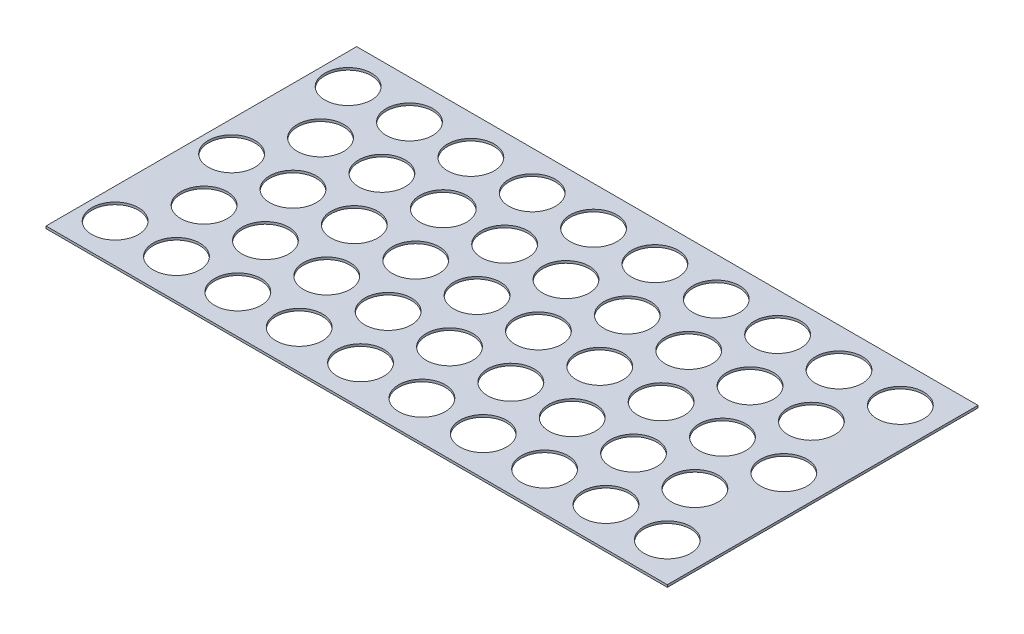
SolidWorks part; units mm, degrees
ref_plane "Front Plane" through (0, 0, 0) normal (0, 0, 1) x (1, 0, 0)
ref_plane "Top Plane" through (0, 0, 0) normal (0, 1, 0) x (1, 0, 0)
ref_plane "Right Plane" through (0, 0, 0) normal (1, 0, 0) x (0, 0, -1)
sketch "Sketch1" plane through (0, 0, 0) normal (0, 1, 0) x (1, 0, 0)
  line L1 (-100.118, 57.1397) -> (103.082, 57.1397)
  line L2 (-100.118, 57.1397) -> (-100.118, -44.4603)
  line L3 (-100.118, -44.4603) -> (103.082, -44.4603)
  line L4 (103.082, 57.1397) -> (103.082, -44.4603)
  dimension "D1" = 203.2
  dimension "D2" = 101.6
extrude "Boss-Extrude2" add sketch "Sketch1" against normal blind 0.762 contours L4 L1 L2 L3
sketch "Sketch2" plane through (0, 0, 0) normal (0, 1, 0) x (1, 0, 0)
  line L0 (103.082, -44.4603) -> (103.082, -31.7603) construction
  line L1 (103.082, -31.7603) -> (90.382, -31.7603)
  line L2 (103.082, -31.7603) -> (-49896.918, -31.7603) construction
  line L3 (90.382, -31.7603) -> (90.382, 6.3397) construction
  line L4 (103.082, -44.4603) -> (103.082, 57.1397)
  line L5 (103.082, 57.1397) -> (-100.118, 57.1397)
  line L6 (-100.118, 57.1397) -> (-100.118, -44.4603)
  line L7 (-100.118, -44.4603) -> (103.082, -44.4603)
  line L8 (103.082, -44.4603) -> (103.082, 57.1397)
  line L9 (103.082, 57.1397) -> (-100.118, 57.1397)
  line L10 (-100.118, 57.1397) -> (-100.118, -44.4603)
  line L11 (-100.118, -44.4603) -> (103.082, -44.4603)
  line L12 (90.382, 6.3397) -> (-49909.618, 6.3397) construction
  line L13 (90.382, 6.3397) -> (90.382, 44.4397) construction
  line L14 (90.382, 44.4397) -> (-49909.618, 44.4397) construction
  line L15 (90.382, -31.7603) -> (80.349, -31.7603) construction
  line L16 (80.349, -31.7603) -> (80.349, 49968.2397) construction
  line L17 (90.382, -31.7603) -> (90.382, -12.7103) construction
  line L18 (90.382, -12.7103) -> (-49909.618, -12.7103) construction
  line L19 (90.382, 6.3397) -> (90.382, 25.3897) construction
  line L20 (90.382, 25.3897) -> (-49909.618, 25.3897) construction
  line L21 (90.382, -12.7103) -> (80.349, -12.7103) construction
  line L22 (80.349, -12.7103) -> (80.349, 25.3897) construction
  circle A0 centre (90.382, -31.7603) radius 7.62
  circle A1 centre (90.382, 6.3397) radius 7.62
  circle A2 centre (90.382, 44.4397) radius 7.62
  circle A3 centre (70.316, -31.7603) radius 7.62
  circle A4 centre (50.25, -31.7603) radius 7.62
  circle A5 centre (30.184, -31.7603) radius 7.62
  circle A6 centre (10.118, -31.7603) radius 7.62
  circle A7 centre (-9.948, -31.7603) radius 7.62
  circle A8 centre (-30.014, -31.7603) radius 7.62
  circle A9 centre (-50.08, -31.7603) radius 7.62
  circle A10 centre (-70.146, -31.7603) radius 7.62
  circle A11 centre (-90.212, -31.7603) radius 7.62
  circle A12 centre (70.316, 6.3397) radius 7.62
  circle A13 centre (50.25, 6.3397) radius 7.62
  circle A14 centre (30.184, 6.3397) radius 7.62
  circle A15 centre (10.118, 6.3397) radius 7.62
  circle A16 centre (-9.948, 6.3397) radius 7.62
  circle A17 centre (-30.014, 6.3397) radius 7.62
  circle A18 centre (-50.08, 6.3397) radius 7.62
  circle A19 centre (-70.146, 6.3397) radius 7.62
  circle A20 centre (-90.212, 6.3397) radius 7.62
  circle A21 centre (70.316, 44.4397) radius 7.62
  circle A22 centre (50.25, 44.4397) radius 7.62
  circle A23 centre (30.184, 44.4397) radius 7.62
  circle A24 centre (10.118, 44.4397) radius 7.62
  circle A25 centre (-9.948, 44.4397) radius 7.62
  circle A26 centre (-30.014, 44.4397) radius 7.62
  circle A27 centre (-50.08, 44.4397) radius 7.62
  circle A28 centre (-70.146, 44.4397) radius 7.62
  circle A29 centre (-90.212, 44.4397) radius 7.62
  circle A30 centre (80.349, -12.7103) radius 7.62
  circle A31 centre (80.349, 25.3897) radius 7.62
  circle A32 centre (60.283, -12.7103) radius 7.62
  circle A33 centre (60.283, 25.3897) radius 7.62
  circle A34 centre (40.217, -12.7103) radius 7.62
  circle A35 centre (40.217, 25.3897) radius 7.62
  circle A36 centre (20.151, -12.7103) radius 7.62
  circle A37 centre (20.151, 25.3897) radius 7.62
  circle A38 centre (0.085, -12.7103) radius 7.62
  circle A39 centre (0.085, 25.3897) radius 7.62
  circle A40 centre (-19.981, -12.7103) radius 7.62
  circle A41 centre (-19.981, 25.3897) radius 7.62
  circle A42 centre (-40.047, -12.7103) radius 7.62
  circle A43 centre (-40.047, 25.3897) radius 7.62
  circle A44 centre (-60.113, -12.7103) radius 7.62
  circle A45 centre (-60.113, 25.3897) radius 7.62
  circle A46 centre (-80.179, -12.7103) radius 7.62
  circle A47 centre (-80.179, 25.3897) radius 7.62
  dimension "D4" = 15.24
  dimension "D12" = 15.24
  dimension "D13" = 15.24
  dimension "D2" = 12.7
  dimension "D3" = 12.7
  dimension "D5" = 38.1
  dimension "D6" = 38.1
  dimension "D11" = 10.033
  dimension "D1" = 0
  dimension "D7" = 3
  dimension "D8" = 10
  dimension "D9" = 10
  dimension "D10" = 10
  dimension "D14" = 9
extrude "Cut-Extrude1" cut sketch "Sketch2" against normal through all both and the other way through all
